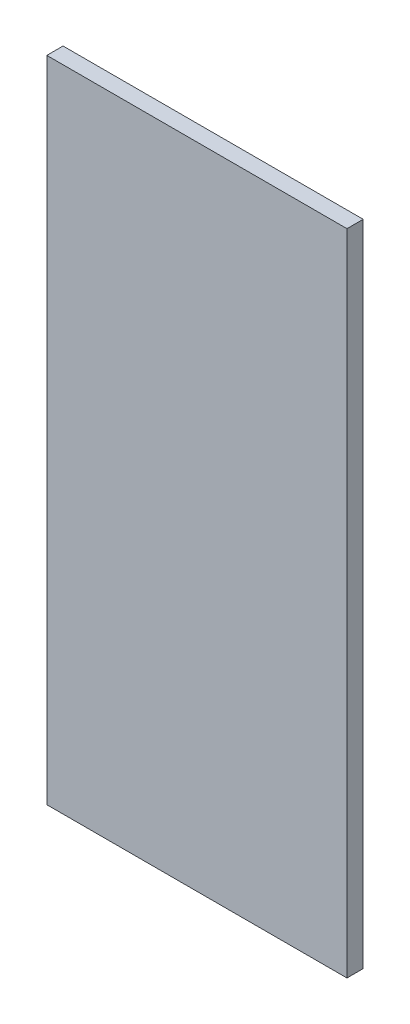
SolidWorks part; units mm, degrees
ref_plane "Front Plane" through (0, 0, 0) normal (0, 0, 1) x (1, 0, 0)
ref_plane "Top Plane" through (0, 0, 0) normal (0, 1, 0) x (1, 0, 0)
ref_plane "Right Plane" through (0, 0, 0) normal (1, 0, 0) x (0, 0, -1)
sketch "Sketch1" plane through (0, 0, 0) normal (0, 0, 1) x (1, 0, 0)
  line L1 (0, 0) -> (37, 0)
  line L2 (0, 0) -> (0, 80)
  line L3 (0, 80) -> (37, 80)
  line L4 (37, 0) -> (37, 80)
  dimension "D1" = 80
  dimension "D2" = 37
extrude "Boss-Extrude1" add sketch "Sketch1" along normal blind 2
